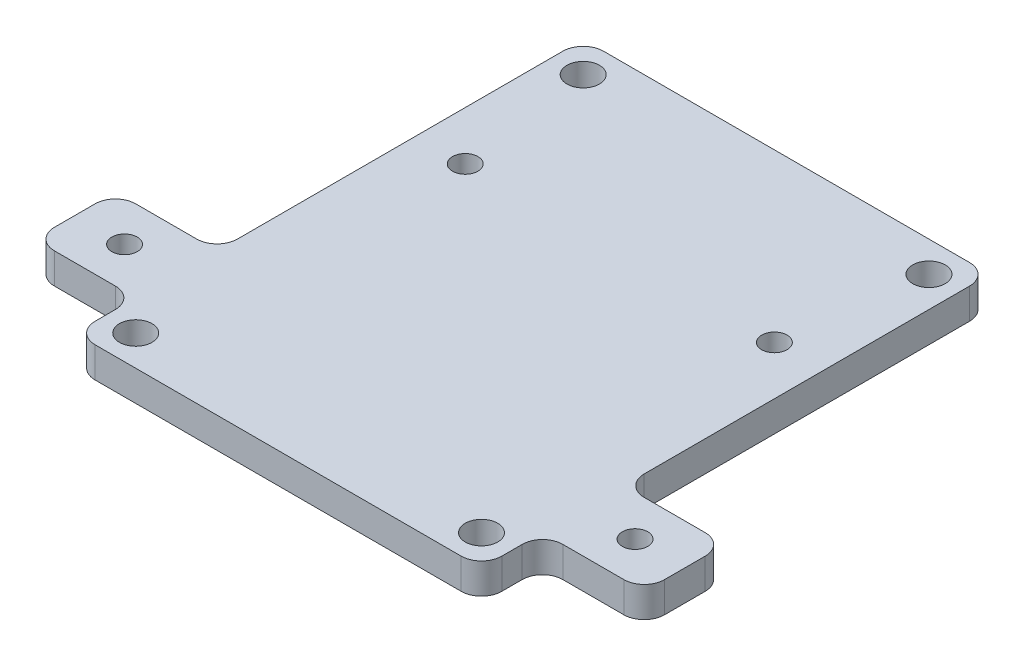
SolidWorks part; units mm, degrees
material "松木"
ref_plane "前视基准面" through (0, 0, 0) normal (0, 0, 1) x (1, 0, 0)
ref_plane "上视基准面" through (0, 0, 0) normal (0, 1, 0) x (1, 0, 0)
ref_plane "右视基准面" through (0, 0, 0) normal (1, 0, 0) x (0, 0, -1)
sketch "草图1" plane through (0, 0, 0) normal (0, 1, 0) x (1, 0, 0)
  line L1 (-18, 25) -> (18, 25)
  line L2 (-20, 23) -> (-20, -23)
  line L3 (-18, -25) -> (18, -25)
  line L4 (20, 23) -> (20, -23)
  line L5 (0, -25) -> (0, 25) construction
  line L6 (-20, 0) -> (20, 0) construction
  arc A0 (18, 25) -> (20, 23) centre (18, 23) cw
  arc A1 (-20, -23) -> (-18, -25) centre (-18, -23) ccw
  arc A2 (-18, 25) -> (-20, 23) centre (-18, 23) ccw
  arc A3 (18, -25) -> (20, -23) centre (18, -23) ccw
  point P0 (0, 0)
  point P6 (20, 25)
  point P12 (-20, -25)
  point P15 (-20, 25)
  dimension "D3" = 2
  dimension "D1" = 50
  dimension "D2" = 40
extrude "凸台-拉伸1" add sketch "草图1" along normal blind 3
sketch "草图4" plane through (0, 3, 0) normal (0, 1, 0) x (1, 0, 0)
  line L0 (-18, -25) -> (18, -25) construction
  line L1 (-28, -11) -> (28, -11)
  line L2 (-30, -13) -> (-30, -17)
  line L3 (-28, -19) -> (28, -19)
  line L4 (30, -13) -> (30, -17)
  line L5 (0, -19) -> (0, -11) construction
  line L6 (-30, -15) -> (30, -15) construction
  arc A0 (28, -11) -> (30, -13) centre (28, -13) cw
  arc A1 (-30, -17) -> (-28, -19) centre (-28, -17) ccw
  arc A2 (-28, -11) -> (-30, -13) centre (-28, -13) ccw
  arc A3 (28, -19) -> (30, -17) centre (28, -17) ccw
  point P0 (0, -15)
  dimension "D1" = 2
  dimension "D2" = 60
  dimension "D3" = 8
  dimension "D4" = 10
extrude "凸台-拉伸2" add sketch "草图4" against normal up to surface (3 mm away) up to face at (0, 0, 0)
sketch "草图2" plane through (0, 3, 0) normal (0, 1, 0) x (1, 0, 0)
  line L0 (0, 11.6691) -> (0, -11.164) construction
  line L1 (-30, -15) -> (30, -15) construction
  line L2 (-30, -13) -> (-30, -17) construction
  line L4 (30, -17) -> (30, -13) construction
  circle A0 centre (-25.1, -15) radius 1.25
  circle A1 centre (-15.2, 8.6) radius 1.25
  circle A2 centre (15.2, 8.6) radius 1.25
  circle A3 centre (25.1, -15) radius 1.25
  dimension "D1" = 2.5
  dimension "D2" = 50.2
  dimension "D3" = 30.4
  dimension "D4" = 23.6
extrude "切除-拉伸1" cut sketch "草图2" against normal blind 3
sketch "草图3" plane through (0, 3, 0) normal (0, 1, 0) x (1, 0, 0)
  line L0 (0, 19.4142) -> (0, -24.2682) construction
  line L1 (18, 25) -> (-18, 25) construction
  line L2 (-10.1104, 0) -> (12.7652, 0) construction
  line L3 (-20, 23) -> (-20, -11) construction
  circle A0 centre (-17, 22) radius 1.6
  circle A1 centre (-17, -22) radius 1.6
  circle A2 centre (17, -22) radius 1.6
  circle A3 centre (17, 22) radius 1.6
  dimension "D1" = 3.2
  dimension "D2" = 3
  dimension "D3" = 3
extrude "切除-拉伸2" cut sketch "草图3" against normal blind 3
fillet "圆角1" radius 2 4 edges at (-20, 1.5, 11) (20, 1.5, 11) (20, 1.5, 19) (-20, 1.5, 19)
